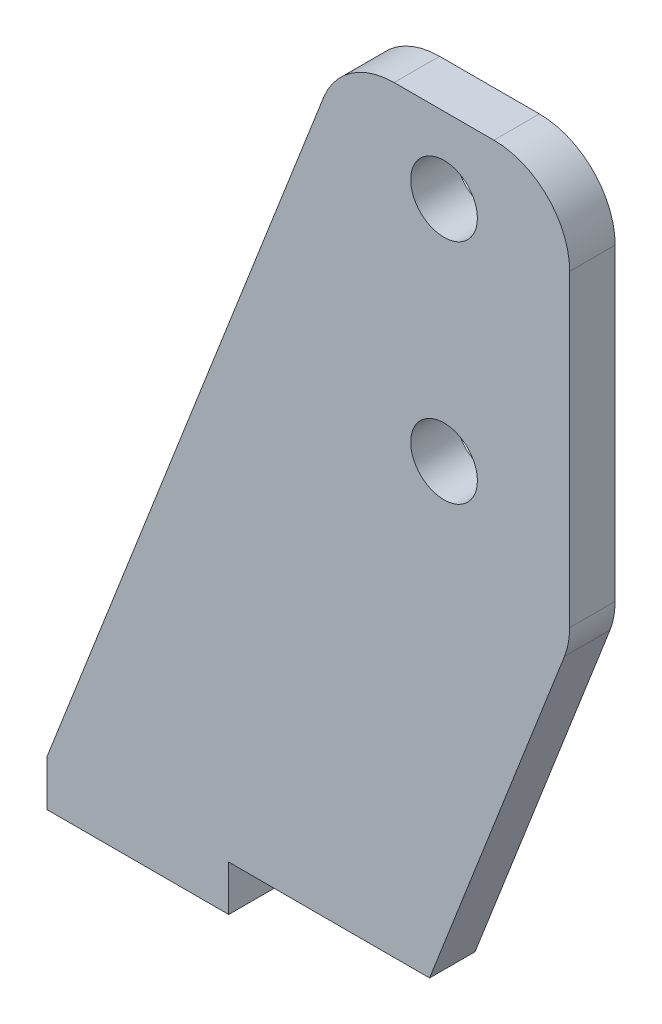
SolidWorks part; units mm, degrees
ref_plane "Front Plane" through (0, 0, 0) normal (0, 0, 1) x (1, 0, 0)
ref_plane "Top Plane" through (0, 0, 0) normal (0, 1, 0) x (1, 0, 0)
ref_plane "Right Plane" through (0, 0, 0) normal (1, 0, 0) x (0, 0, -1)
sketch "Sketch1" plane through (0, 0, 0) normal (0, 0, 1) x (1, 0, 0)
  line L0 (0, 0) -> (18.2585, 46.8167)
  line L1 (22.9168, 50) -> (29.5, 50)
  line L2 (34.5, 45) -> (34.5, 43.4179)
  line L3 (34.5, 43.4179) -> (34.5, 24.6477)
  line L4 (34.1583, 22.831) -> (25.2542, 0)
  line L5 (25.2542, 0) -> (0, 0)
  line L6 (0, 0) -> (0, -3)
  line L7 (0, -3) -> (12, -3)
  line L8 (12, -3) -> (12, 0)
  circle A0 centre (26.2084, 45) radius 2.2
  circle A1 centre (26.2084, 30) radius 2.2
  arc A2 (34.1583, 22.831) -> (34.5, 24.6477) centre (29.5, 24.6477) ccw
  arc A3 (34.5, 45) -> (29.5, 50) centre (29.5, 45) ccw
  arc A4 (22.9168, 50) -> (18.2585, 46.8167) centre (22.9168, 45) ccw
  point P18 (34.5, 50)
  point P21 (19.5, 50)
  point P22 (26.2084, 50)
  dimension "D5" = 15
  dimension "D6" = 5
  dimension "D8" = 5
  dimension "D9" = 0
  dimension "D1" = 22.5
  dimension "D2" = 15
  dimension "D3" = 12
  dimension "D4" = 50
  dimension "D7" = 3
extrude "Boss-Extrude1" add sketch "Sketch1" along normal blind 3 contours L5 L4 L3 L2 L1 L0 | L7 L8 L5 L6
